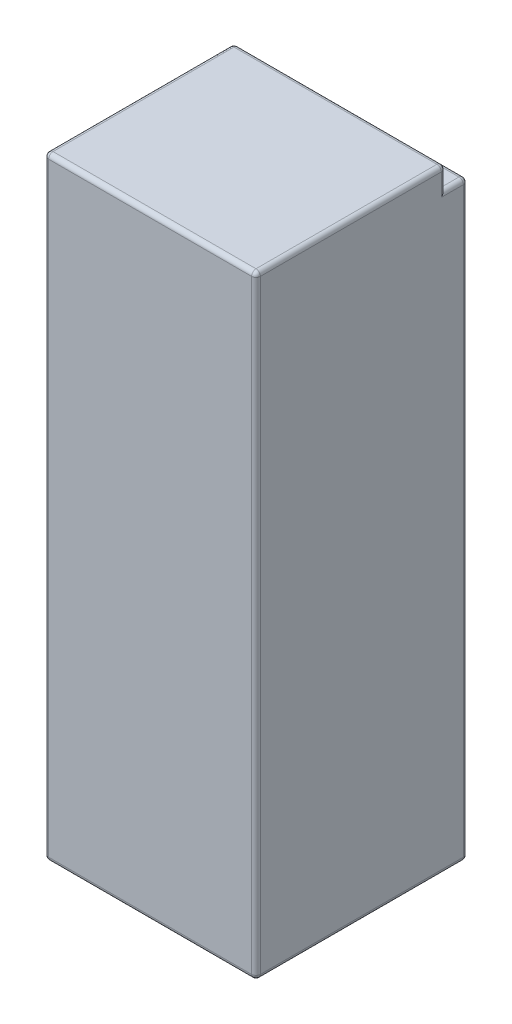
SolidWorks part; units mm, degrees
ref_plane "Front Plane" through (0, 0, 0) normal (0, 0, 1) x (1, 0, 0)
ref_plane "Top Plane" through (0, 0, 0) normal (0, 1, 0) x (1, 0, 0)
ref_plane "Right Plane" through (0, 0, 0) normal (1, 0, 0) x (0, 0, -1)
sketch "Sketch1" plane through (0, 0, 0) normal (0, 1, 0) x (1, 0, 0)
  line L1 (24, -24) -> (-24, -24)
  line L2 (24, -24) -> (24, 24)
  line L3 (24, 24) -> (-24, 24)
  line L4 (-24, -24) -> (-24, 24)
  line L5 (24, -24) -> (-24, 24) construction
  line L6 (24, 24) -> (-24, -24) construction
  point P0 (0, 0)
  dimension "D1" = 48
extrude "Boss-Extrude1" add sketch "Sketch1" along normal mid plane 139
sketch "Sketch2" plane through (0, 0, 0) normal (1, 0, 0) x (0, 0, -1)
  line L1 (24, 69.5) -> (19, 69.5)
  line L2 (24, 69.5) -> (24, 64.5)
  line L3 (24, 64.5) -> (19, 64.5)
  line L4 (19, 69.5) -> (19, 64.5)
  dimension "D1" = 5
extrude "Cut-Extrude1" cut sketch "Sketch2" against normal through all both and the other way through all
fillet "Fillet1" radius 1 17 edges at (24, 67, -19) (24, 64.5, -21.5) (-24, 67, -19) (-24, 64.5, -21.5) (0, 69.5, -19) (0, 64.5, -24) (-24, -69.5, 0) (0, -69.5, 24) (24, -69.5, 0) (0, -69.5, -24) (-24, 69.5, 2.5) (0, 69.5, 24) (24, 69.5, 2.5) (-24, -2.5, -24) (24, 0, 24) (-24, 0, 24) (24, -2.5, -24)
